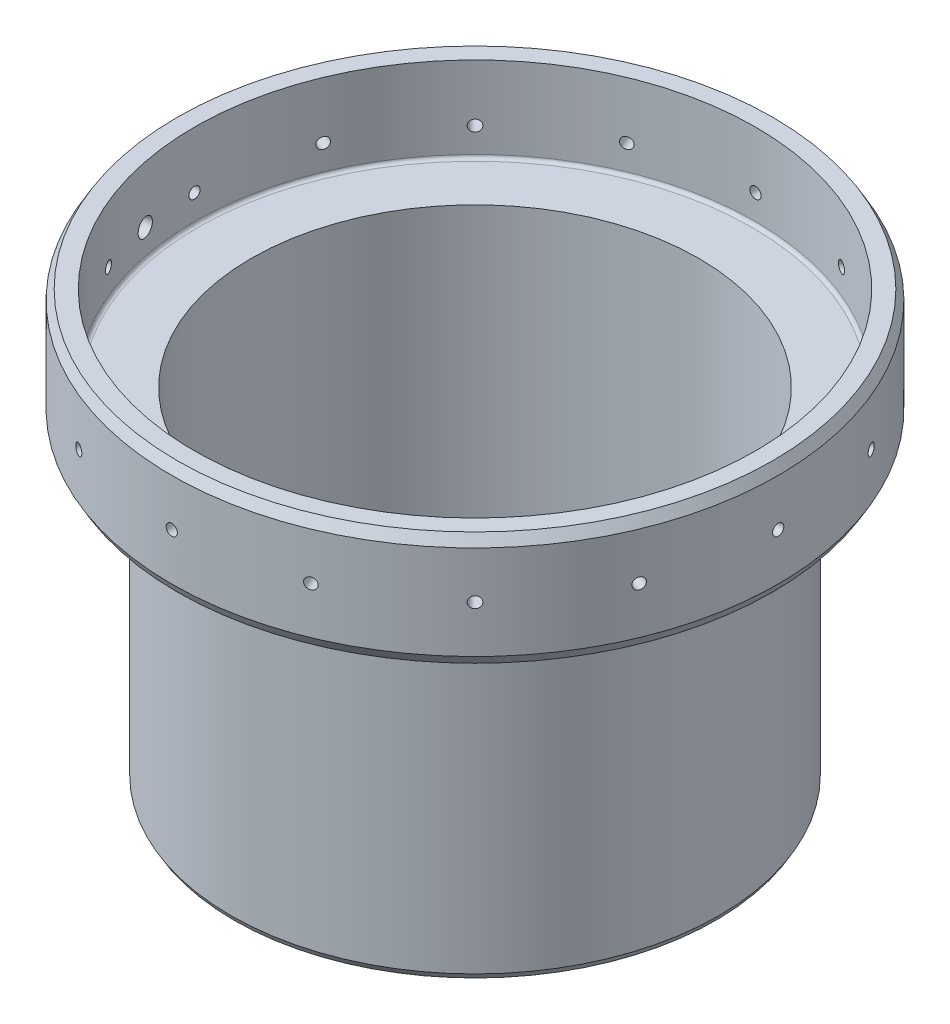
SolidWorks part; units mm, degrees
material "6061-T6 (SS)"
ref_plane "Front Plane" through (0, 0, 0) normal (0, 0, 1) x (1, 0, 0)
ref_plane "Top Plane" through (0, 0, 0) normal (0, 1, 0) x (1, 0, 0)
ref_plane "Right Plane" through (0, 0, 0) normal (1, 0, 0) x (0, 0, -1)
sketch "Sketch1" plane through (0, 0, 0) normal (0, 0, 1) x (1, 0, 0)
  line L0 (0, 0) -> (0, 9.1321) construction
  line L1 (0, 0) -> (-62.6618, 0) construction
  line L2 (-62.6618, 0) -> (-67.7418, 0)
  line L3 (-67.7418, 0) -> (-67.7418, -25.4)
  line L4 (-67.7418, -25.4) -> (-54.5465, -25.4)
  line L5 (-54.5465, -25.4) -> (-54.5465, -95.25)
  line L6 (-54.5465, -95.25) -> (-49.9745, -95.25)
  line L7 (-49.9745, -95.25) -> (-49.9745, -19.05)
  line L8 (-49.9745, -19.05) -> (-62.6618, -19.05)
  line L9 (-62.6618, -19.05) -> (-62.6618, 0)
  dimension "D1" = 5.08
  dimension "D2" = 67.7418
  dimension "D3" = 25.4
  dimension "D4" = 6.35
  dimension "D5" = 69.85
  dimension "D6" = 4.572
  dimension "D7" = 54.5465
revolve "Revolve6" add sketch "Sketch1" angle 360 about L0
sketch "Sketch2" plane through (0, 0, 0) normal (0, 1, 0) x (1, 0, 0)
  line L0 (0, 0) -> (-67.7418, 0) construction
  line L1 (0, 0) -> (-66.4402, -13.2158) construction
  circle A0 centre (0, 0) radius 67.7418 construction
  dimension "D1" = 11.25
ref_plane "Plane1" through (-67.7418, 0, 0) normal (-1, 0, 0) x (0, 0, 1)
sketch "Sketch3" plane through (-67.7418, 0, 0) normal (-1, 0, 0) x (0, 0, 1)
  line L0 (0, 0) -> (0, -12.7) construction
  dimension "D1" = 12.7
hole_wizard "Tap Drill for M3x0.5 Tap1" positions "Sketch5" profile "Sketch4" hole size "M3x0.5" standard "Ansi Metric"
sketch "Sketch5" plane through (-67.7418, 0, 0) normal (-1, 0, 0) x (0, 0, 1)
  point P1 (0, -12.7)
sketch "Sketch4" plane through (-67.7418, -12.7, 0) normal (0, 1, 0) x (0, 0, 1)
  line L0 (0, 0) -> (0, 10.9111)
  line L1 (0, 10.9111) -> (1.25, 10.16)
  line L2 (1.25, 10.16) -> (1.25, 0)
  line L5 (1.25, 0) -> (0, 0)
  line L10 (0, 10.9111) -> (-1.25, 10.16) construction
  line L11 (0, -6.35) -> (0, 107.95) construction
  dimension "Hole Dia." = 2.5
  dimension "Hole Depth" = 10.16
  dimension "Drill Angle" = 118
pattern_circular "CirPattern1" count 16 over 360 about axis through (0, 0, 0) along (0, -1, 0) of "Tap Drill for M3x0.5 Tap1"
ref_plane "Plane2" through (-66.4402, 0, 13.2158) normal (-0.9808, 0, 0.1951) x (0.1951, 0, 0.9808)
sketch "Sketch6" plane through (-66.4402, 0, 13.2158) normal (-0.9808, 0, 0.1951) x (0.1951, 0, 0.9808)
  line L0 (0, 0) -> (0, -12.7) construction
  dimension "D1" = 12.7
hole_wizard "Tap Drill for #10-32 Tap1" positions "Sketch8" profile "Sketch7" hole size "#10-32" standard "Ansi Inch"
sketch "Sketch8" plane through (-66.4402, 0, 13.2158) normal (-0.9808, 0, 0.1951) x (0.1951, 0, 0.9808)
  point P1 (0, -12.7)
sketch "Sketch7" plane through (-66.4402, -12.7, 13.2158) normal (0, 1, 0) x (0.1951, 0, 0.9808)
  line L0 (0, 0) -> (0, 11.3733)
  line L1 (0, 11.3733) -> (2.0193, 10.16)
  line L2 (2.0193, 10.16) -> (2.0193, 0)
  line L5 (2.0193, 0) -> (0, 0)
  line L10 (0, 11.3733) -> (-2.0193, 10.16) construction
  line L11 (0, -6.35) -> (0, 107.95) construction
  dimension "Hole Dia." = 4.0386
  dimension "Hole Depth" = 10.16
  dimension "Drill Angle" = 118
sketch "Sketch9" plane through (0, -95.25, 0) normal (0, -1, 0) x (1, 0, 0)
  line L0 (54.5465, 0) -> (49.9745, 0) construction
  circle A1 centre (0, 0) radius 54.5465 construction
  circle A2 centre (0, 0) radius 49.9745 construction
  point P9 (52.2605, 0)
hole_wizard "Tap Drill for #4-40 Tap1" positions "3DSketch1" profile "Sketch10" hole size "#4-40" standard "Ansi Inch"
sketch3d "3DSketch1"
  point P0 (52.2605, -95.25, 0)
sketch "Sketch10" plane through (52.2605, -95.25, 0) normal (1, 0, 0) x (0, 0, -1)
  line L0 (0, 0) -> (0, 18.4592)
  line L1 (0, 18.4592) -> (1.1303, 17.78)
  line L2 (1.1303, 17.78) -> (1.1303, 0)
  line L5 (1.1303, 0) -> (0, 0)
  line L10 (0, 18.4592) -> (-1.1303, 17.78) construction
  line L11 (0, -6.35) -> (0, 107.95) construction
  dimension "Hole Dia." = 2.2606
  dimension "Hole Depth" = 17.78
  dimension "Drill Angle" = 118
pattern_circular "CirPattern2" count 16 over 360 about axis through (0, 0, 0) along (0, 1, 0) of "Tap Drill for #4-40 Tap1"
chamfer "Chamfer2" distance 1.27 angle 60 2 edges at (0, -25.4, -67.7418) (0, 0, -67.7418)
chamfer "Chamfer4" distance 0.762 angle 60 1 edges at (0, -95.25, -54.5465)
chamfer "Chamfer5" distance 0.762 angle 60 1 edges at (0, -95.25, -49.9745)
fillet "Fillet1" radius 0.762 2 edges at (0, -25.4, -54.5465) (0, -19.05, -62.6618)
